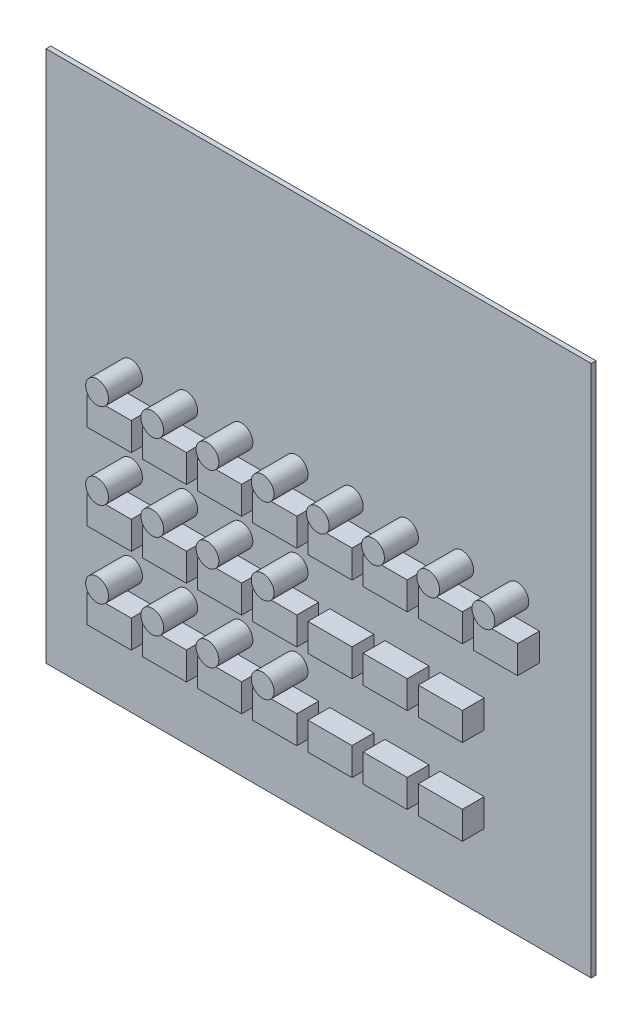
SolidWorks part; units mm, degrees
ref_plane "Front Plane" through (0, 0, 0) normal (0, 0, 1) x (1, 0, 0)
ref_plane "Top Plane" through (0, 0, 0) normal (0, 1, 0) x (1, 0, 0)
ref_plane "Right Plane" through (0, 0, 0) normal (1, 0, 0) x (0, 0, -1)
sketch "Sketch1" plane through (0, 0, 0) normal (0, 0, 1) x (1, 0, 0)
  line L0 (0, 0) -> (0, 177.8)
  line L1 (0, 177.8) -> (182.118, 177.8)
  line L2 (182.118, 177.8) -> (182.118, 0)
  line L3 (182.118, 0) -> (0, 0)
extrude "BOARD" add sketch "Sketch1" along normal blind 1.5921 separate body
ref_plane "Plane1" through (0, 0, 1.5921) normal (0, 0, 1) x (1, 0, 0)
sketch "Sketch2" plane through (0, 0, 1.5921) normal (0, 0, 1) x (1, 0, 0)
  circle A0 centre (83.7097, 41.1988) radius 3.81
extrude "LED-KINGBRIGHT_3P_2P54-1" add sketch "Sketch2" along normal blind 11.3538 separate body
sketch "Sketch3" plane through (0, 0, 1.5921) normal (0, 0, 1) x (1, 0, 0)
  circle A0 centre (65.2722, 41.1988) radius 3.81
extrude "LED-KINGBRIGHT_3P_2P54-2" add sketch "Sketch3" along normal blind 11.3538 separate body
sketch "Sketch4" plane through (0, 0, 1.5921) normal (0, 0, 1) x (1, 0, 0)
  circle A0 centre (46.8347, 41.1988) radius 3.81
extrude "LED-KINGBRIGHT_3P_2P54-3" add sketch "Sketch4" along normal blind 11.3538 separate body
sketch "Sketch5" plane through (0, 0, 1.5921) normal (0, 0, 1) x (1, 0, 0)
  circle A0 centre (28.3972, 41.1988) radius 3.81
extrude "LED-KINGBRIGHT_3P_2P54-4" add sketch "Sketch5" along normal blind 11.3538 separate body
sketch "Sketch6" plane through (0, 0, 1.5921) normal (0, 0, 1) x (1, 0, 0)
  circle A0 centre (83.7097, 69.7738) radius 3.81
extrude "LED-KINGBRIGHT_3P_2P54-5" add sketch "Sketch6" along normal blind 11.3538 separate body
sketch "Sketch7" plane through (0, 0, 1.5921) normal (0, 0, 1) x (1, 0, 0)
  circle A0 centre (65.2722, 69.7738) radius 3.81
extrude "LED-KINGBRIGHT_3P_2P54-6" add sketch "Sketch7" along normal blind 11.3538 separate body
sketch "Sketch8" plane through (0, 0, 1.5921) normal (0, 0, 1) x (1, 0, 0)
  circle A0 centre (46.8347, 69.7738) radius 3.81
extrude "LED-KINGBRIGHT_3P_2P54-7" add sketch "Sketch8" along normal blind 11.3538 separate body
sketch "Sketch9" plane through (0, 0, 1.5921) normal (0, 0, 1) x (1, 0, 0)
  circle A0 centre (28.3972, 69.7738) radius 3.81
extrude "LED-KINGBRIGHT_3P_2P54-8" add sketch "Sketch9" along normal blind 11.3538 separate body
sketch "Sketch10" plane through (0, 0, 1.5921) normal (0, 0, 1) x (1, 0, 0)
  circle A0 centre (157.4597, 98.3488) radius 3.81
extrude "LED-KINGBRIGHT_3P_2P54-9" add sketch "Sketch10" along normal blind 11.3538 separate body
sketch "Sketch11" plane through (0, 0, 1.5921) normal (0, 0, 1) x (1, 0, 0)
  circle A0 centre (139.0222, 98.3488) radius 3.81
extrude "LED-KINGBRIGHT_3P_2P54-10" add sketch "Sketch11" along normal blind 11.3538 separate body
sketch "Sketch12" plane through (0, 0, 1.5921) normal (0, 0, 1) x (1, 0, 0)
  circle A0 centre (120.5847, 98.3488) radius 3.81
extrude "LED-KINGBRIGHT_3P_2P54-11" add sketch "Sketch12" along normal blind 11.3538 separate body
sketch "Sketch13" plane through (0, 0, 1.5921) normal (0, 0, 1) x (1, 0, 0)
  circle A0 centre (102.1472, 98.3488) radius 3.81
extrude "LED-KINGBRIGHT_3P_2P54-12" add sketch "Sketch13" along normal blind 11.3538 separate body
sketch "Sketch14" plane through (0, 0, 1.5921) normal (0, 0, 1) x (1, 0, 0)
  circle A0 centre (83.7097, 98.3488) radius 3.81
extrude "LED-KINGBRIGHT_3P_2P54-13" add sketch "Sketch14" along normal blind 11.3538 separate body
sketch "Sketch15" plane through (0, 0, 1.5921) normal (0, 0, 1) x (1, 0, 0)
  circle A0 centre (65.2722, 98.3488) radius 3.81
extrude "LED-KINGBRIGHT_3P_2P54-14" add sketch "Sketch15" along normal blind 11.3538 separate body
sketch "Sketch16" plane through (0, 0, 1.5921) normal (0, 0, 1) x (1, 0, 0)
  circle A0 centre (46.8347, 98.3488) radius 3.81
extrude "LED-KINGBRIGHT_3P_2P54-15" add sketch "Sketch16" along normal blind 11.3538 separate body
sketch "Sketch17" plane through (0, 0, 1.5921) normal (0, 0, 1) x (1, 0, 0)
  circle A0 centre (28.3972, 98.3488) radius 3.81
extrude "LED-KINGBRIGHT_3P_2P54-16" add sketch "Sketch17" along normal blind 11.3538 separate body
sketch "Sketch18" plane through (0, 0, 1.5921) normal (0, 0, 1) x (1, 0, 0)
  line L0 (131.6562, 25.3238) -> (131.6562, 34.5948)
  line L1 (131.6562, 34.5948) -> (146.3882, 34.5948)
  line L2 (146.3882, 34.5948) -> (146.3882, 25.3238)
  line L3 (146.3882, 25.3238) -> (131.6562, 25.3238)
extrude "SWITCH-MCDTS2-1" add sketch "Sketch18" along normal blind 7.3 separate body
sketch "Sketch19" plane through (0, 0, 1.5921) normal (0, 0, 1) x (1, 0, 0)
  line L0 (113.2187, 25.3238) -> (113.2187, 34.5948)
  line L1 (113.2187, 34.5948) -> (127.9507, 34.5948)
  line L2 (127.9507, 34.5948) -> (127.9507, 25.3238)
  line L3 (127.9507, 25.3238) -> (113.2187, 25.3238)
extrude "SWITCH-MCDTS2-2" add sketch "Sketch19" along normal blind 7.3 separate body
sketch "Sketch20" plane through (0, 0, 1.5921) normal (0, 0, 1) x (1, 0, 0)
  line L0 (94.7812, 25.3238) -> (94.7812, 34.5948)
  line L1 (94.7812, 34.5948) -> (109.5132, 34.5948)
  line L2 (109.5132, 34.5948) -> (109.5132, 25.3238)
  line L3 (109.5132, 25.3238) -> (94.7812, 25.3238)
extrude "SWITCH-MCDTS2-3" add sketch "Sketch20" along normal blind 7.3 separate body
sketch "Sketch21" plane through (0, 0, 1.5921) normal (0, 0, 1) x (1, 0, 0)
  line L0 (76.3437, 25.3238) -> (76.3437, 34.5948)
  line L1 (76.3437, 34.5948) -> (91.0757, 34.5948)
  line L2 (91.0757, 34.5948) -> (91.0757, 25.3238)
  line L3 (91.0757, 25.3238) -> (76.3437, 25.3238)
extrude "SWITCH-MCDTS2-4" add sketch "Sketch21" along normal blind 7.3 separate body
sketch "Sketch22" plane through (0, 0, 1.5921) normal (0, 0, 1) x (1, 0, 0)
  line L0 (57.9062, 25.3238) -> (57.9062, 34.5948)
  line L1 (57.9062, 34.5948) -> (72.6382, 34.5948)
  line L2 (72.6382, 34.5948) -> (72.6382, 25.3238)
  line L3 (72.6382, 25.3238) -> (57.9062, 25.3238)
extrude "SWITCH-MCDTS2-5" add sketch "Sketch22" along normal blind 7.3 separate body
sketch "Sketch23" plane through (0, 0, 1.5921) normal (0, 0, 1) x (1, 0, 0)
  line L0 (39.4687, 25.3238) -> (39.4687, 34.5948)
  line L1 (39.4687, 34.5948) -> (54.2007, 34.5948)
  line L2 (54.2007, 34.5948) -> (54.2007, 25.3238)
  line L3 (54.2007, 25.3238) -> (39.4687, 25.3238)
extrude "SWITCH-MCDTS2-6" add sketch "Sketch23" along normal blind 7.3 separate body
sketch "Sketch24" plane through (0, 0, 1.5921) normal (0, 0, 1) x (1, 0, 0)
  line L0 (21.0312, 25.3238) -> (21.0312, 34.5948)
  line L1 (21.0312, 34.5948) -> (35.7632, 34.5948)
  line L2 (35.7632, 34.5948) -> (35.7632, 25.3238)
  line L3 (35.7632, 25.3238) -> (21.0312, 25.3238)
extrude "SWITCH-MCDTS2-7" add sketch "Sketch24" along normal blind 7.3 separate body
sketch "Sketch25" plane through (0, 0, 1.5921) normal (0, 0, 1) x (1, 0, 0)
  line L0 (131.6562, 53.8988) -> (131.6562, 63.1698)
  line L1 (131.6562, 63.1698) -> (146.3882, 63.1698)
  line L2 (146.3882, 63.1698) -> (146.3882, 53.8988)
  line L3 (146.3882, 53.8988) -> (131.6562, 53.8988)
extrude "SWITCH-MCDTS2-8" add sketch "Sketch25" along normal blind 7.3 separate body
sketch "Sketch26" plane through (0, 0, 1.5921) normal (0, 0, 1) x (1, 0, 0)
  line L0 (113.2187, 53.8988) -> (113.2187, 63.1698)
  line L1 (113.2187, 63.1698) -> (127.9507, 63.1698)
  line L2 (127.9507, 63.1698) -> (127.9507, 53.8988)
  line L3 (127.9507, 53.8988) -> (113.2187, 53.8988)
extrude "SWITCH-MCDTS2-9" add sketch "Sketch26" along normal blind 7.3 separate body
sketch "Sketch27" plane through (0, 0, 1.5921) normal (0, 0, 1) x (1, 0, 0)
  line L0 (94.7812, 53.8988) -> (94.7812, 63.1698)
  line L1 (94.7812, 63.1698) -> (109.5132, 63.1698)
  line L2 (109.5132, 63.1698) -> (109.5132, 53.8988)
  line L3 (109.5132, 53.8988) -> (94.7812, 53.8988)
extrude "SWITCH-MCDTS2-10" add sketch "Sketch27" along normal blind 7.3 separate body
sketch "Sketch28" plane through (0, 0, 1.5921) normal (0, 0, 1) x (1, 0, 0)
  line L0 (76.3437, 53.8988) -> (76.3437, 63.1698)
  line L1 (76.3437, 63.1698) -> (91.0757, 63.1698)
  line L2 (91.0757, 63.1698) -> (91.0757, 53.8988)
  line L3 (91.0757, 53.8988) -> (76.3437, 53.8988)
extrude "SWITCH-MCDTS2-11" add sketch "Sketch28" along normal blind 7.3 separate body
sketch "Sketch29" plane through (0, 0, 1.5921) normal (0, 0, 1) x (1, 0, 0)
  line L0 (57.9062, 53.8988) -> (57.9062, 63.1698)
  line L1 (57.9062, 63.1698) -> (72.6382, 63.1698)
  line L2 (72.6382, 63.1698) -> (72.6382, 53.8988)
  line L3 (72.6382, 53.8988) -> (57.9062, 53.8988)
extrude "SWITCH-MCDTS2-12" add sketch "Sketch29" along normal blind 7.3 separate body
sketch "Sketch30" plane through (0, 0, 1.5921) normal (0, 0, 1) x (1, 0, 0)
  line L0 (39.4687, 53.8988) -> (39.4687, 63.1698)
  line L1 (39.4687, 63.1698) -> (54.2007, 63.1698)
  line L2 (54.2007, 63.1698) -> (54.2007, 53.8988)
  line L3 (54.2007, 53.8988) -> (39.4687, 53.8988)
extrude "SWITCH-MCDTS2-13" add sketch "Sketch30" along normal blind 7.3 separate body
sketch "Sketch31" plane through (0, 0, 1.5921) normal (0, 0, 1) x (1, 0, 0)
  line L0 (21.0312, 53.8988) -> (21.0312, 63.1698)
  line L1 (21.0312, 63.1698) -> (35.7632, 63.1698)
  line L2 (35.7632, 63.1698) -> (35.7632, 53.8988)
  line L3 (35.7632, 53.8988) -> (21.0312, 53.8988)
extrude "SWITCH-MCDTS2-14" add sketch "Sketch31" along normal blind 7.3 separate body
sketch "Sketch32" plane through (0, 0, 1.5921) normal (0, 0, 1) x (1, 0, 0)
  line L0 (150.0937, 82.4738) -> (150.0937, 91.7448)
  line L1 (150.0937, 91.7448) -> (164.8257, 91.7448)
  line L2 (164.8257, 91.7448) -> (164.8257, 82.4738)
  line L3 (164.8257, 82.4738) -> (150.0937, 82.4738)
extrude "SWITCH-MCDTS2-15" add sketch "Sketch32" along normal blind 7.3 separate body
sketch "Sketch33" plane through (0, 0, 1.5921) normal (0, 0, 1) x (1, 0, 0)
  line L0 (131.6562, 82.4738) -> (131.6562, 91.7448)
  line L1 (131.6562, 91.7448) -> (146.3882, 91.7448)
  line L2 (146.3882, 91.7448) -> (146.3882, 82.4738)
  line L3 (146.3882, 82.4738) -> (131.6562, 82.4738)
extrude "SWITCH-MCDTS2-16" add sketch "Sketch33" along normal blind 7.3 separate body
sketch "Sketch34" plane through (0, 0, 1.5921) normal (0, 0, 1) x (1, 0, 0)
  line L0 (113.2187, 82.4738) -> (113.2187, 91.7448)
  line L1 (113.2187, 91.7448) -> (127.9507, 91.7448)
  line L2 (127.9507, 91.7448) -> (127.9507, 82.4738)
  line L3 (127.9507, 82.4738) -> (113.2187, 82.4738)
extrude "SWITCH-MCDTS2-17" add sketch "Sketch34" along normal blind 7.3 separate body
sketch "Sketch35" plane through (0, 0, 1.5921) normal (0, 0, 1) x (1, 0, 0)
  line L0 (94.7812, 82.4738) -> (94.7812, 91.7448)
  line L1 (94.7812, 91.7448) -> (109.5132, 91.7448)
  line L2 (109.5132, 91.7448) -> (109.5132, 82.4738)
  line L3 (109.5132, 82.4738) -> (94.7812, 82.4738)
extrude "SWITCH-MCDTS2-18" add sketch "Sketch35" along normal blind 7.3 separate body
sketch "Sketch36" plane through (0, 0, 1.5921) normal (0, 0, 1) x (1, 0, 0)
  line L0 (76.3437, 82.4738) -> (76.3437, 91.7448)
  line L1 (76.3437, 91.7448) -> (91.0757, 91.7448)
  line L2 (91.0757, 91.7448) -> (91.0757, 82.4738)
  line L3 (91.0757, 82.4738) -> (76.3437, 82.4738)
extrude "SWITCH-MCDTS2-19" add sketch "Sketch36" along normal blind 7.3 separate body
sketch "Sketch37" plane through (0, 0, 1.5921) normal (0, 0, 1) x (1, 0, 0)
  line L0 (57.9062, 82.4738) -> (57.9062, 91.7448)
  line L1 (57.9062, 91.7448) -> (72.6382, 91.7448)
  line L2 (72.6382, 91.7448) -> (72.6382, 82.4738)
  line L3 (72.6382, 82.4738) -> (57.9062, 82.4738)
extrude "SWITCH-MCDTS2-20" add sketch "Sketch37" along normal blind 7.3 separate body
sketch "Sketch38" plane through (0, 0, 1.5921) normal (0, 0, 1) x (1, 0, 0)
  line L0 (39.4687, 82.4738) -> (39.4687, 91.7448)
  line L1 (39.4687, 91.7448) -> (54.2007, 91.7448)
  line L2 (54.2007, 91.7448) -> (54.2007, 82.4738)
  line L3 (54.2007, 82.4738) -> (39.4687, 82.4738)
extrude "SWITCH-MCDTS2-21" add sketch "Sketch38" along normal blind 7.3 separate body
sketch "Sketch39" plane through (0, 0, 1.5921) normal (0, 0, 1) x (1, 0, 0)
  line L0 (21.0312, 82.4738) -> (21.0312, 91.7448)
  line L1 (21.0312, 91.7448) -> (35.7632, 91.7448)
  line L2 (35.7632, 91.7448) -> (35.7632, 82.4738)
  line L3 (35.7632, 82.4738) -> (21.0312, 82.4738)
extrude "SWITCH-MCDTS2-22" add sketch "Sketch39" along normal blind 7.3 separate body
